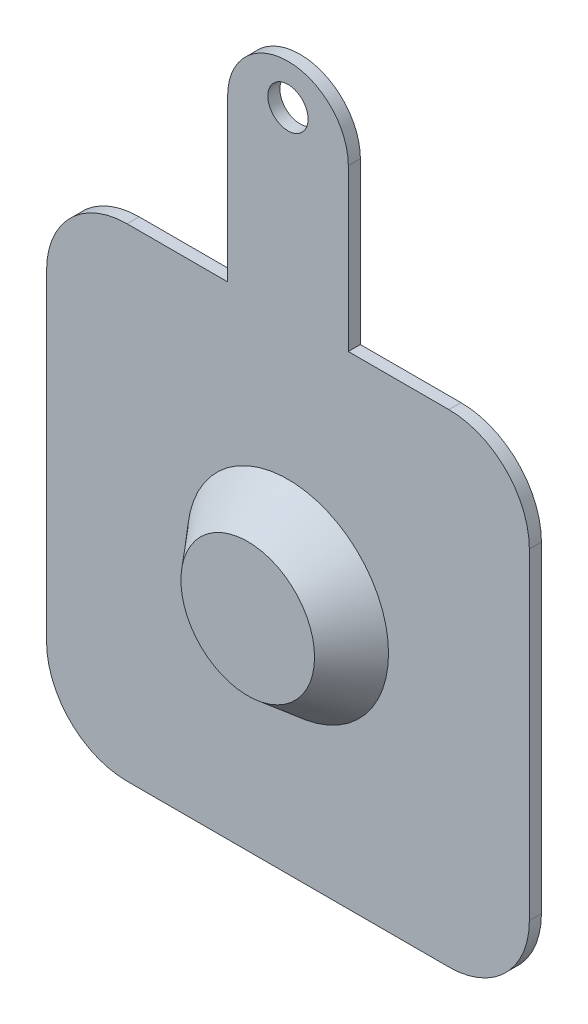
SolidWorks part; units mm, degrees
ref_plane "前视基准面" through (0, 0, 0) normal (0, 0, 1) x (1, 0, 0)
ref_plane "上视基准面" through (0, 0, 0) normal (0, 1, 0) x (1, 0, 0)
ref_plane "右视基准面" through (0, 0, 0) normal (1, 0, 0) x (0, 0, -1)
other "Configuration Table"
sketch "草图1" plane through (0, 0, 0) normal (0, 0, 1) x (1, 0, 0)
  line L0 (-7.5, 12) -> (-12, 12)
  line L1 (0, 0) -> (-12, 0)
  line L2 (0, 0) -> (0, 12)
  line L3 (0, 12) -> (-4.5, 12)
  line L4 (-12, 0) -> (-12, 12)
  line L6 (-7.5, 12) -> (-7.5, 16)
  line L8 (-4.5, 12) -> (-4.5, 16)
  arc A0 (-4.5, 16) -> (-7.5, 16) centre (-6, 16) ccw
  dimension "D6" = 1.5
  dimension "D1" = 12
  dimension "D2" = 12
  dimension "D3" = 4
  dimension "D4" = 4.5
  dimension "D5" = 4.5
extrude "凸台-拉伸1" add sketch "草图1" along normal blind 0.3
fillet "圆角1" radius 2 4 edges at (0, 0, 0.15) (-12, 0, 0.15) (-12, 12, 0.15) (0, 12, 0.15)
sketch "草图2" plane through (0, 0, 0.3) normal (0, 0, 1) x (1, 0, 0)
  line L0 (-11.4142, 11.4142) -> (0.3751, -0.3751) construction
  line L1 (-0.5858, 11.4142) -> (-11.6996, 0.3004) construction
  arc A0 (-10, 12) -> (-12, 10) centre (-10, 10) ccw construction
  arc A1 (0, 10) -> (-2, 12) centre (-2, 10) ccw construction
  circle A2 centre (-6, 6) radius 2.5
  dimension "D1" = 5
extrude "凸台-拉伸2" add sketch "草图2" along normal blind 1 draft 40
sketch "草图3" plane through (0, 0, 0.3) normal (0, 0, 1) x (1, 0, 0)
  line L0 (-6, 17.5) -> (-6, 16.5) construction
  arc A0 (-4.5, 16) -> (-7.5, 16) centre (-6, 16) ccw construction
  circle A1 centre (-6, 16.5) radius 0.5
  dimension "D2" = 1
  dimension "D1" = 1
extrude "切除-拉伸1" cut sketch "草图3" against normal blind 1
